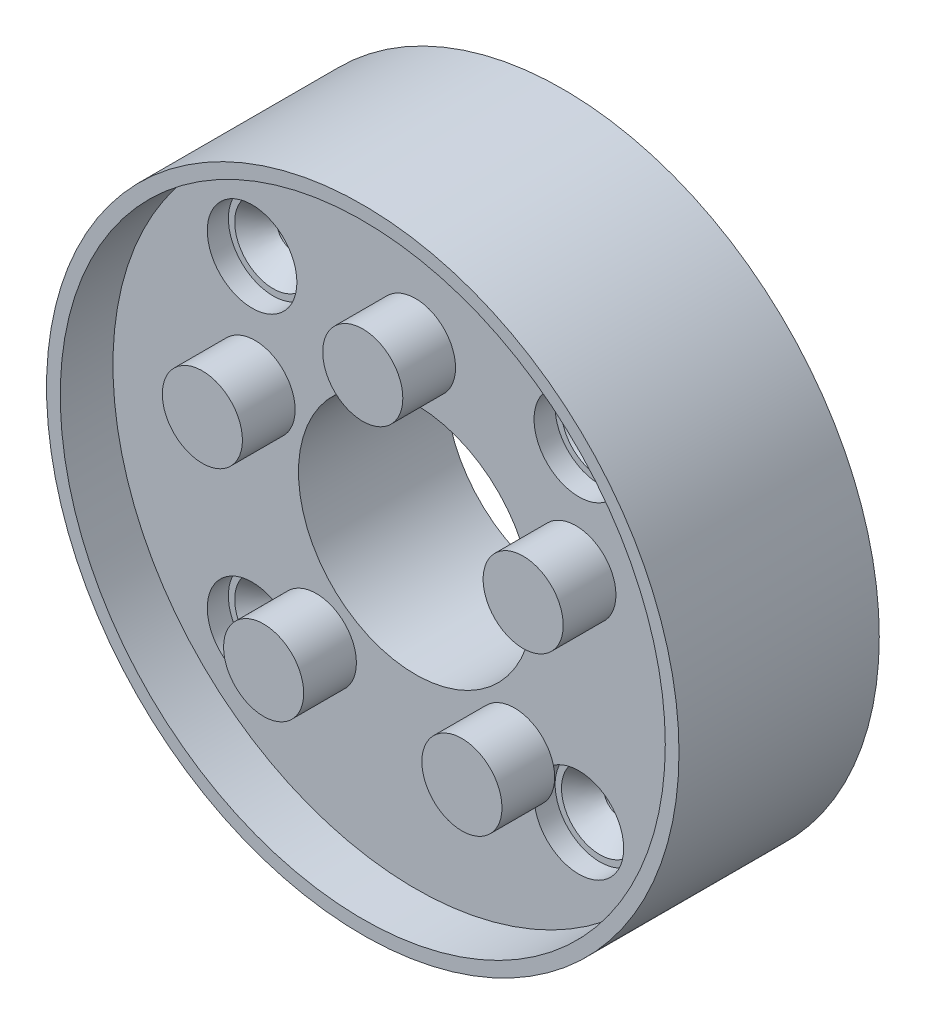
SolidWorks part; units mm, degrees
ref_plane "Plan de face" through (0, 0, 0) normal (0, 0, 1) x (1, 0, 0)
ref_plane "Plan de dessus" through (0, 0, 0) normal (0, 1, 0) x (1, 0, 0)
ref_plane "Plan de droite" through (0, 0, 0) normal (1, 0, 0) x (0, 0, -1)
sketch "Esquisse1" plane through (0, 0, 0) normal (0, 0, 1) x (1, 0, 0)
  circle A0 centre (0, 0) radius 30
  circle A1 centre (0, 0) radius 11.1
  circle A2 centre (-15.5, 15.5) radius 1.65
  circle A3 centre (15.5, 15.5) radius 1.65
  circle A4 centre (15.5, -15.5) radius 1.65
  circle A5 centre (-15.5, -15.5) radius 1.65
  point P9 (-60, 0)
  point P22 (0, 0)
  dimension "D1" = 60
  dimension "D2" = 22.2
  dimension "D7" = 3.3
  dimension "D5" = 15.5
  dimension "D8" = 4
extrude "Boss.-Extru.1" add sketch "Esquisse1" along normal blind 14
sketch "Esquisse3" plane through (0, 0, 14) normal (0, 0, 1) x (1, 0, 0)
  circle A0 centre (0, 16) radius 3.8
  circle A1 centre (15.2169, 4.9443) radius 3.8
  circle A2 centre (9.4046, -12.9443) radius 3.8
  circle A3 centre (-9.4046, -12.9443) radius 3.8
  circle A4 centre (-15.2169, 4.9443) radius 3.8
  circle A5 centre (0, 0) radius 28.7
  circle A7 centre (0, 0) radius 30
  point P13 (0, 0)
  point P15 (6.0149, 14.8264)
  point P16 (0, 16)
  circle M7 centre (0, 0) radius 30
  dimension "D2" = 7.6
  dimension "D4" = 57.4
  dimension "D1" = 16
  dimension "D3" = 5
extrude "Boss.-Extru.2" add sketch "Esquisse3" along normal blind 5 contours A5 M7 | A4 | A0 | A2 | A3 | A1
sketch "Esquisse4" plane through (0, 0, 14) normal (0, 0, 1) x (1, 0, 0)
  circle A0 centre (-15.5, 15.5) radius 4.25
  circle A2 centre (-15.5, 15.5) radius 1.65 construction
  circle A3 centre (15.5, 15.5) radius 4.25
  circle A4 centre (15.5, -15.5) radius 4.25
  circle A5 centre (-15.5, -15.5) radius 4.25
  point P16 (0, 0)
  dimension "D1" = 8.5
  dimension "D2" = 4
extrude "Enlèv. mat.-Extru.1" cut sketch "Esquisse4" against normal blind 2
chamfer "Chanfrein1" distance 2 angle 45 4 edges at (-13.85, 15.5, 12) (-13.85, -15.5, 12) (17.15, -15.5, 12) (17.15, 15.5, 12)
